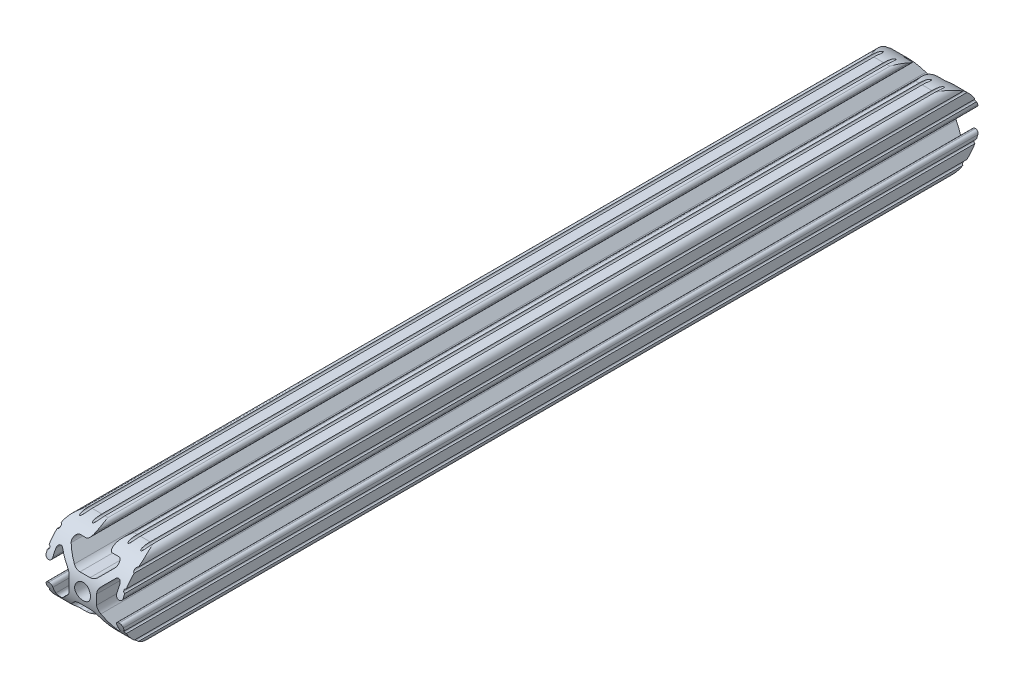
SolidWorks part; units mm, degrees
material "6061-T6 (SS)"
ref_plane "Front Plane" through (0, 0, 0) normal (0, 0, 1) x (1, 0, 0)
ref_plane "Top Plane" through (0, 0, 0) normal (0, 1, 0) x (1, 0, 0)
ref_plane "Right Plane" through (0, 0, 0) normal (1, 0, 0) x (0, 0, -1)
sketch "Sketch1" plane through (0, 0, 0) normal (0, 0, 1) x (1, 0, 0)
  line L88 (-7.1797, -8.6452) -> (-3.9523, -5.4237)
  line L89 (-1.7093, -4.4958) -> (1.7093, -4.4958)
  line L90 (3.9523, -5.4237) -> (7.1797, -8.6452)
  line L91 (6.4164, -10.4902) -> (4.2875, -10.4902)
  line L92 (3.2385, -11.5392) -> (3.2385, -11.651)
  line L93 (4.2875, -12.7) -> (5.3171, -12.7)
  line L94 (6.3331, -12.7) -> (9.5504, -12.7)
  line L95 (12.7, -9.5504) -> (12.7, -6.3331)
  line L96 (12.7, -5.3171) -> (12.7, -4.2875)
  line L97 (11.651, -3.2385) -> (11.5392, -3.2385)
  line L98 (10.4902, -4.2875) -> (10.4902, -6.4021)
  line L99 (8.7371, -7.1294) -> (5.441, -3.8408)
  line L100 (4.5085, -1.5932) -> (4.5085, 1.5932)
  line L101 (5.441, 3.8408) -> (8.7371, 7.1294)
  line L102 (10.4902, 6.4021) -> (10.4902, 4.2875)
  line L103 (11.5392, 3.2385) -> (11.651, 3.2385)
  line L104 (12.7, 4.2875) -> (12.7, 5.3171)
  line L105 (12.7, 6.3331) -> (12.7, 9.5504)
  line L106 (9.5504, 12.7) -> (6.3331, 12.7)
  line L107 (5.3171, 12.7) -> (4.2875, 12.7)
  line L108 (3.2385, 11.651) -> (3.2385, 11.5392)
  line L109 (4.2875, 10.4902) -> (6.4768, 10.4902)
  line L110 (7.207, 8.7244) -> (3.8983, 5.4232)
  line L111 (1.6558, 4.4958) -> (-1.6558, 4.4958)
  line L112 (-3.8983, 5.4232) -> (-7.207, 8.7244)
  line L113 (-6.4768, 10.4902) -> (-4.2875, 10.4902)
  line L114 (-3.2385, 11.5392) -> (-3.2385, 11.651)
  line L115 (-4.2875, 12.7) -> (-5.3171, 12.7)
  line L116 (-6.3331, 12.7) -> (-9.5504, 12.7)
  line L117 (-12.7, 9.5504) -> (-12.7, 6.3331)
  line L118 (-12.7, 5.3171) -> (-12.7, 4.2875)
  line L119 (-11.651, 3.2385) -> (-11.5392, 3.2385)
  line L120 (-10.4902, 4.2875) -> (-10.4902, 6.4021)
  line L121 (-8.7371, 7.1294) -> (-5.441, 3.8408)
  line L122 (-4.5085, 1.5932) -> (-4.5085, -1.5932)
  line L123 (-5.441, -3.8408) -> (-8.7371, -7.1294)
  line L124 (-10.4902, -6.4021) -> (-10.4902, -4.2875)
  line L125 (-11.5392, -3.2385) -> (-11.651, -3.2385)
  line L126 (-12.7, -4.2875) -> (-12.7, -5.3171)
  line L127 (-12.7, -6.3331) -> (-12.7, -9.5504)
  line L128 (-9.5504, -12.7) -> (-6.3331, -12.7)
  line L129 (-5.3171, -12.7) -> (-4.2875, -12.7)
  line L130 (-3.2385, -11.651) -> (-3.2385, -11.5392)
  line L131 (-4.2875, -10.4902) -> (-6.4164, -10.4902)
  circle A1 centre (0, 0) radius 2.6035
  arc A104 (-7.1797, -8.6452) -> (-6.4164, -10.4902) centre (-6.4164, -9.4098) ccw
  arc A105 (-1.7093, -4.4958) -> (-3.9523, -5.4237) centre (-1.7093, -7.6708) ccw
  arc A106 (3.9523, -5.4237) -> (1.7093, -4.4958) centre (1.7093, -7.6708) ccw
  arc A107 (6.4164, -10.4902) -> (7.1797, -8.6452) centre (6.4164, -9.4098) ccw
  arc A108 (4.2875, -10.4902) -> (3.2385, -11.5392) centre (4.2875, -11.5392) ccw
  arc A109 (3.2385, -11.651) -> (4.2875, -12.7) centre (4.2875, -11.651) ccw
  arc A110 (6.3331, -12.7) -> (5.3171, -12.7) centre (5.8251, -12.7) ccw
  arc A111 (10.5664, -12.6998) -> (9.5504, -12.7) centre (10.0584, -12.7) ccw
  arc A112 (10.5664, -12.6998) -> (12.6998, -10.5664) centre (10.5918, -10.5918) ccw
  arc A113 (12.7, -9.5504) -> (12.6998, -10.5664) centre (12.7, -10.0584) ccw
  arc A114 (12.7, -5.3171) -> (12.7, -6.3331) centre (12.7, -5.8251) ccw
  arc A115 (12.7, -4.2875) -> (11.651, -3.2385) centre (11.651, -4.2875) ccw
  arc A116 (11.5392, -3.2385) -> (10.4902, -4.2875) centre (11.5392, -4.2875) ccw
  arc A117 (8.7371, -7.1294) -> (10.4902, -6.4021) centre (9.4628, -6.4021) ccw
  arc A118 (4.5085, -1.5932) -> (5.441, -3.8408) centre (7.6835, -1.5932) ccw
  arc A119 (5.441, 3.8408) -> (4.5085, 1.5932) centre (7.6835, 1.5932) ccw
  arc A120 (10.4902, 6.4021) -> (8.7371, 7.1294) centre (9.4628, 6.4021) ccw
  arc A121 (10.4902, 4.2875) -> (11.5392, 3.2385) centre (11.5392, 4.2875) ccw
  arc A122 (11.651, 3.2385) -> (12.7, 4.2875) centre (11.651, 4.2875) ccw
  arc A123 (12.7, 6.3331) -> (12.7, 5.3171) centre (12.7, 5.8251) ccw
  arc A124 (12.6998, 10.5664) -> (12.7, 9.5504) centre (12.7, 10.0584) ccw
  arc A125 (12.6998, 10.5664) -> (10.5664, 12.6998) centre (10.5918, 10.5918) ccw
  arc A126 (9.5504, 12.7) -> (10.5664, 12.6998) centre (10.0584, 12.7) ccw
  arc A127 (5.3171, 12.7) -> (6.3331, 12.7) centre (5.8251, 12.7) ccw
  arc A128 (4.2875, 12.7) -> (3.2385, 11.651) centre (4.2875, 11.651) ccw
  arc A129 (3.2385, 11.5392) -> (4.2875, 10.4902) centre (4.2875, 11.5392) ccw
  arc A130 (7.207, 8.7244) -> (6.4768, 10.4902) centre (6.4768, 9.4563) ccw
  arc A131 (1.6558, 4.4958) -> (3.8983, 5.4232) centre (1.6558, 7.6708) ccw
  arc A132 (-3.8983, 5.4232) -> (-1.6558, 4.4958) centre (-1.6558, 7.6708) ccw
  arc A133 (-6.4768, 10.4902) -> (-7.207, 8.7244) centre (-6.4768, 9.4563) ccw
  arc A134 (-4.2875, 10.4902) -> (-3.2385, 11.5392) centre (-4.2875, 11.5392) ccw
  arc A135 (-3.2385, 11.651) -> (-4.2875, 12.7) centre (-4.2875, 11.651) ccw
  arc A136 (-6.3331, 12.7) -> (-5.3171, 12.7) centre (-5.8251, 12.7) ccw
  arc A137 (-10.5664, 12.6998) -> (-9.5504, 12.7) centre (-10.0584, 12.7) ccw
  arc A138 (-10.5664, 12.6998) -> (-12.6998, 10.5664) centre (-10.5918, 10.5918) ccw
  arc A139 (-12.7, 9.5504) -> (-12.6998, 10.5664) centre (-12.7, 10.0584) ccw
  arc A140 (-12.7, 5.3171) -> (-12.7, 6.3331) centre (-12.7, 5.8251) ccw
  arc A141 (-12.7, 4.2875) -> (-11.651, 3.2385) centre (-11.651, 4.2875) ccw
  arc A142 (-11.5392, 3.2385) -> (-10.4902, 4.2875) centre (-11.5392, 4.2875) ccw
  arc A143 (-8.7371, 7.1294) -> (-10.4902, 6.4021) centre (-9.4628, 6.4021) ccw
  arc A144 (-4.5085, 1.5932) -> (-5.441, 3.8408) centre (-7.6835, 1.5932) ccw
  arc A145 (-5.441, -3.8408) -> (-4.5085, -1.5932) centre (-7.6835, -1.5932) ccw
  arc A146 (-10.4902, -6.4021) -> (-8.7371, -7.1294) centre (-9.4628, -6.4021) ccw
  arc A147 (-10.4902, -4.2875) -> (-11.5392, -3.2385) centre (-11.5392, -4.2875) ccw
  arc A148 (-11.651, -3.2385) -> (-12.7, -4.2875) centre (-11.651, -4.2875) ccw
  arc A149 (-12.7, -6.3331) -> (-12.7, -5.3171) centre (-12.7, -5.8251) ccw
  arc A150 (-12.6998, -10.5664) -> (-12.7, -9.5504) centre (-12.7, -10.0584) ccw
  arc A151 (-12.6998, -10.5664) -> (-10.5664, -12.6998) centre (-10.5918, -10.5918) ccw
  arc A152 (-9.5504, -12.7) -> (-10.5664, -12.6998) centre (-10.0584, -12.7) ccw
  arc A153 (-5.3171, -12.7) -> (-6.3331, -12.7) centre (-5.8251, -12.7) ccw
  arc A154 (-4.2875, -12.7) -> (-3.2385, -11.651) centre (-4.2875, -11.651) ccw
  arc A155 (-3.2385, -11.5392) -> (-4.2875, -10.4902) centre (-4.2875, -11.5392) ccw
extrude "Boss-Extrude1" add sketch "Sketch1" along normal mid plane 282.575
sketch "Sketch3" plane through (12.7, 0, 0) normal (1, 0, 0) x (0, 0, -1)
  line L0 (-141.2875, 0) -> (141.2875, 0) construction
  line L1 (-141.2875, 12.7) -> (141.2875, 12.7)
  line L2 (-141.2875, 12.7) -> (-141.2875, -12.7)
  line L3 (-141.2875, -12.7) -> (141.2875, -12.7)
  line L4 (141.2875, 12.7) -> (141.2875, -12.7)
  circle A0 centre (-128.5875, 0) radius 12.7
  circle A1 centre (128.5875, 0) radius 12.7
  circle A2 centre (-128.5875, 0) radius 3.175
  circle A3 centre (-103.1875, 0) radius 3.175
  line M9 (141.2875, 6.3331) -> (141.2875, 9.5504)
  line M10 (141.2875, 9.5504) -> (-141.2875, 9.5504)
  line M11 (-141.2875, 9.5504) -> (-141.2875, 6.3331)
  line M12 (-141.2875, 6.3331) -> (141.2875, 6.3331)
  dimension "D1" = 25.4
  dimension "D2" = 6.35
extrude "Cut-Extrude1" cut sketch "Sketch3" against normal through all both and the other way through all contours A0 L2 L3 | A0 M10 M11 M12 | A0 L1 L2 M10 | A0 L2 M12 | L0 A3 | A3 L0 | A2 L0 | L0 A2 | A1 L4 L1 M10 | A1 M12 M9 M10 | A1 L4 M12 | A1 L3 L4
